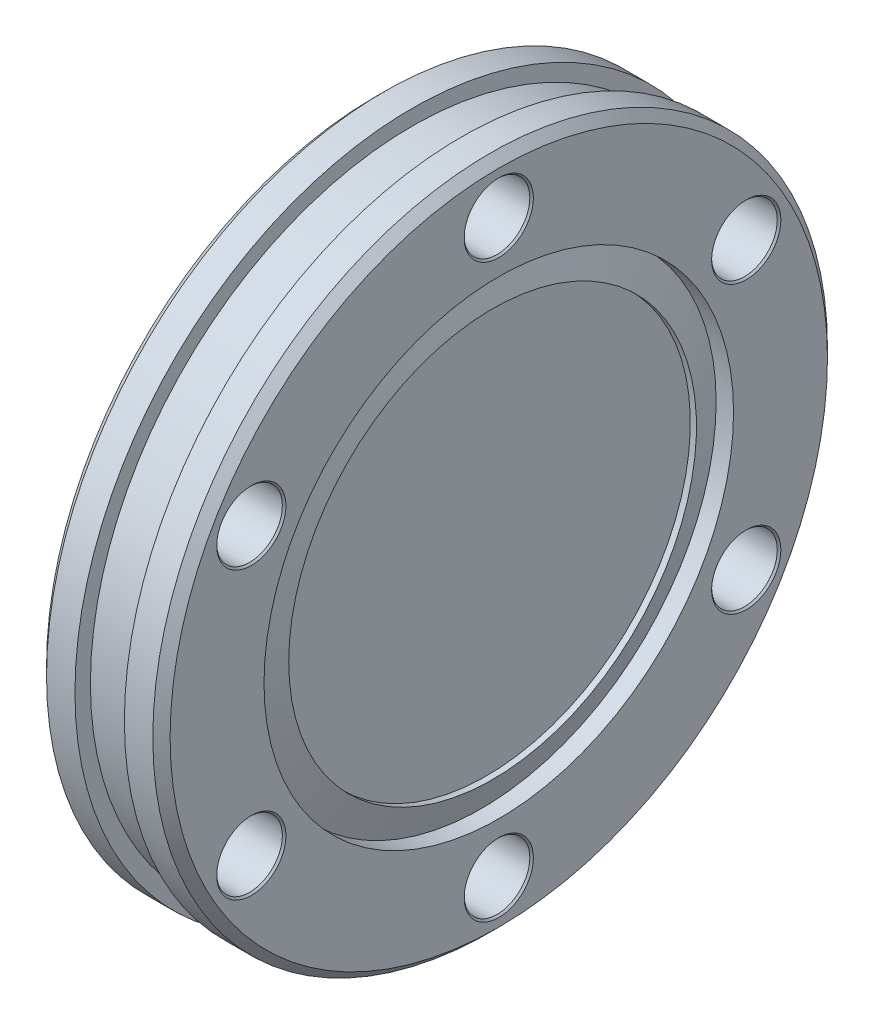
SolidWorks part; units mm, degrees
ref_plane "Alzado" through (0, 0, 0) normal (0, 0, 1) x (1, 0, 0)
ref_plane "Planta" through (0, 0, 0) normal (0, 1, 0) x (1, 0, 0)
ref_plane "Vista lateral" through (0, 0, 0) normal (1, 0, 0) x (0, 0, -1)
ref_plane "Plane1" through (0, 0, 0) normal (0, 0, -1) x (-1, 0, 0)
sketch "Sketch1" plane through (0, 0, 0) normal (0, 0, -1) x (-1, 0, 0)
  line L0 (-5.08, 20.955) -> (-5.08, 0)
  line L1 (-5.08, 0) -> (6.35, 0)
  line L2 (6.35, 0) -> (6.35, 34.671)
  line L3 (6.35, 34.671) -> (2.54, 34.671)
  line L4 (2.54, 34.671) -> (2.54, 33.0835)
  line L5 (2.54, 33.0835) -> (-2.54, 33.0835)
  line L6 (-2.54, 33.0835) -> (-2.54, 34.671)
  line L7 (-2.54, 34.671) -> (-6.35, 34.671)
  line L8 (-6.35, 34.671) -> (-6.35, 24.13)
  line L9 (-6.35, 24.13) -> (-4.5594, 24.13)
  line L10 (-4.5594, 24.13) -> (-5.715, 20.955)
  line L11 (-5.715, 20.955) -> (-5.08, 20.955)
  line L12 (-6.35, 0) -> (6.35, 0) construction
revolve "Revolve1" add sketch "Sketch1" angle 360 about L12
hole_wizard "M6 Clearance Hole1" positions "Sketch3" profile "Sketch2" hole size "M6" standard "ANSI Metric"
sketch "Sketch3" plane through (6.35, 0, 0) normal (1, 0, 0) x (0, 0, -1)
  point P0 (0, 29.3687)
  point P1 (25.4341, 14.6844)
  point P2 (0, -29.3687)
  point P3 (-25.4341, 14.6844)
sketch "Sketch2" plane through (6.35, 29.3687, 0) normal (0, 1, 0) x (0, 0, -1)
  line L0 (0, 0) -> (0, 12.7)
  line L1 (0, 12.7) -> (3.3731, 12.7)
  line L2 (3.3731, 12.7) -> (3.3731, 0)
  line L5 (3.3731, 0) -> (0, 0)
  line L11 (0, -6.35) -> (0, 107.95) construction
  dimension "Thru Hole Dia." = 6.7462
  dimension "Thru Hole Depth" = 12.7
hole_wizard "M6 Clearance Hole2" positions "Sketch5" profile "Sketch4" hole size "M6" standard "ANSI Metric"
sketch "Sketch5" plane through (-6.35, 0, 0) normal (-1, 0, 0) x (0, 0, 1)
  point P0 (25.4341, -14.6844)
  point P1 (-25.4341, -14.6844)
sketch "Sketch4" plane through (-6.35, -14.6844, 25.4341) normal (0, 1, 0) x (0, 0, 1)
  line L0 (0, 0) -> (0, 12.7)
  line L1 (0, 12.7) -> (3.3731, 12.7)
  line L2 (3.3731, 12.7) -> (3.3731, 0)
  line L5 (3.3731, 0) -> (0, 0)
  line L11 (0, -6.35) -> (0, 107.95) construction
  dimension "Thru Hole Dia." = 6.7462
  dimension "Thru Hole Depth" = 12.7
chamfer "Chamfer1" distance 0.1829 angle 45 12 edges at (-6.35, 14.6844, -28.8072) (-6.35, 29.3687, -3.3731) (6.35, -14.6844, 28.8072) (-6.35, -29.3687, -3.3731) (6.35, -14.6844, -22.061) (-6.35, -14.6844, -22.061) (6.35, 29.3687, -3.3731) (6.35, 14.6844, -28.8072) (6.35, -29.3687, -3.3731) (-6.35, 14.6844, 22.061) (6.35, 14.6844, 22.061) (-6.35, -14.6844, 28.8072)
chamfer "Chamfer2" distance 0.889 angle 45 2 edges at (6.35, 0, 34.671) (-6.35, 0, 34.671)
